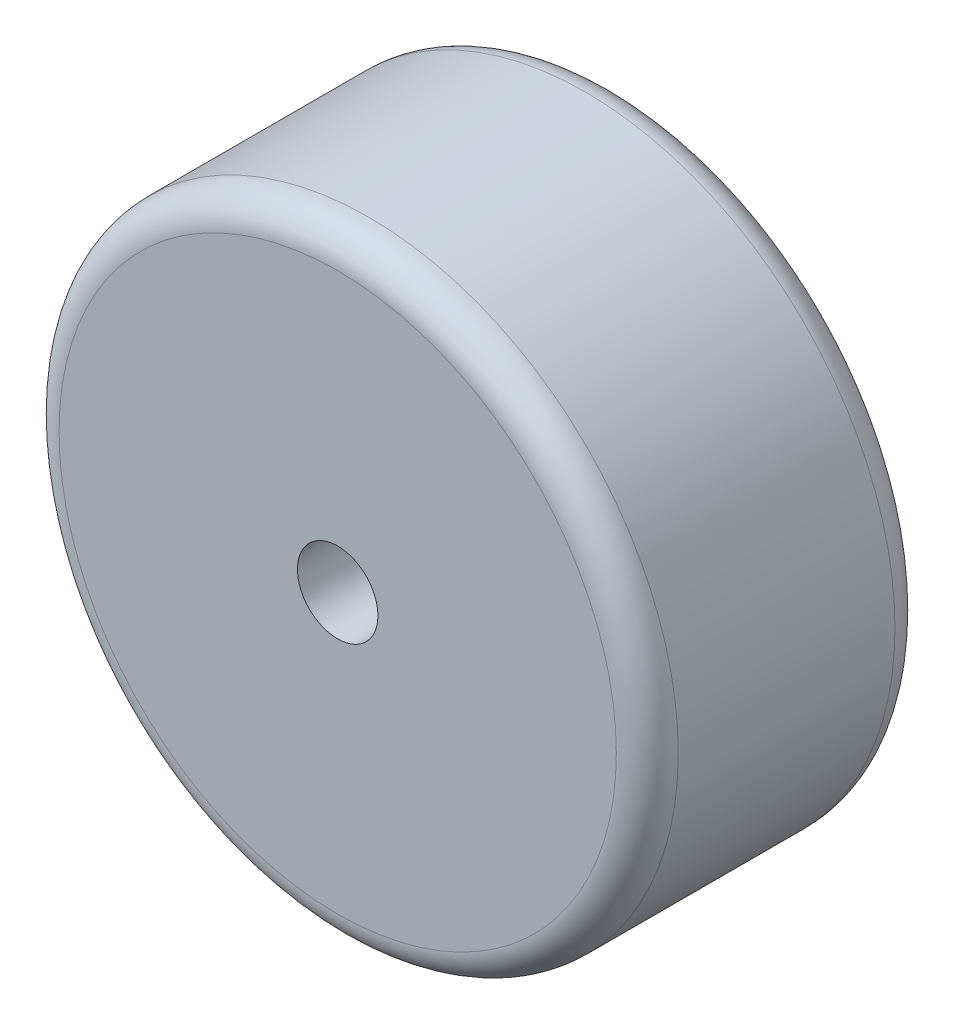
SolidWorks part; units mm, degrees
ref_plane "Plan de face" through (0, 0, 0) normal (0, 0, 1) x (1, 0, 0)
ref_plane "Plan de dessus" through (0, 0, 0) normal (0, 1, 0) x (1, 0, 0)
ref_plane "Plan de droite" through (0, 0, 0) normal (1, 0, 0) x (0, 0, -1)
sketch "Esquisse1" plane through (0, 0, 0) normal (0, 0, 1) x (1, 0, 0)
  circle A0 centre (0, 0) radius 5
  circle A1 centre (0, 0) radius 0.65
  dimension "D1" = 10
  dimension "D2" = 1.3
extrude "Extrusion1" add sketch "Esquisse1" along normal blind 4.5
fillet "Congé1" radius 0.5 2 edges at (5, 0, 0) (5, 0, 4.5)
